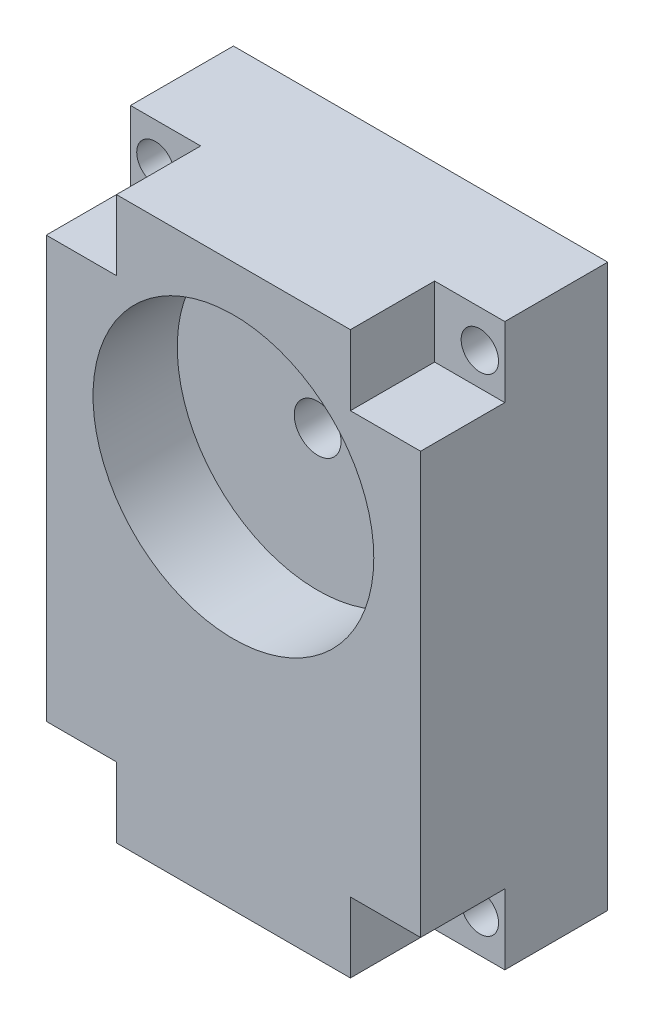
SolidWorks part; units mm, degrees
ref_plane "Front Plane" through (0, 0, 0) normal (0, 0, 1) x (1, 0, 0)
ref_plane "Top Plane" through (0, 0, 0) normal (0, 1, 0) x (1, 0, 0)
ref_plane "Right Plane" through (0, 0, 0) normal (1, 0, 0) x (0, 0, -1)
sketch "Sketch1" plane through (0, 0, 0) normal (0, 0, 1) x (1, 0, 0)
  line L1 (20, -30) -> (-20, -30)
  line L2 (20, -30) -> (20, 30)
  line L3 (20, 30) -> (-20, 30)
  line L4 (-20, -30) -> (-20, 30)
  line L5 (20, -30) -> (-20, 30) construction
  line L6 (20, 30) -> (-20, -30) construction
  point P0 (0, 0)
  dimension "D1" = 40
  dimension "D2" = 60
extrude "Boss-Extrude1" add sketch "Sketch1" along normal blind 20
sketch "Sketch2" plane through (0, 0, 20) normal (0, 0, 1) x (1, 0, 0)
  line L0 (-20, 0) -> (20, 0) construction
  line L1 (-20, 30) -> (-20, -30) construction
  line L2 (20, -30) -> (20, 30) construction
  line L3 (20, 0) -> (0, 0) construction
  line L4 (0, 0) -> (0, 20.25) construction
  circle A0 centre (0, 10.125) radius 15
  dimension "D2" = 30
  dimension "D1" = 20.25
extrude "Cut-Extrude1" cut sketch "Sketch2" against normal blind 9
sketch "Sketch3" plane through (0, 0, 11) normal (0, 0, 1) x (1, 0, 0)
  line L5 (10, -20.25) -> (-10, 20.25) construction
  line L6 (10, 20.25) -> (-10, -20.25) construction
  line L7 (0, 0) -> (20, 30) construction
  line L8 (20, 30) -> (20, 0) construction
  line L9 (20, -30) -> (20, 30) construction
  line L10 (20, 0) -> (0, 0) construction
  line L11 (0, 0) -> (0, 13.6402) construction
  line L12 (0, 0) -> (0, 20.25) construction
  line L13 (20, 30) -> (-20, 30) construction
  line L14 (10, 15) -> (10, 20.25)
  circle A0 centre (17.3333, 26) radius 2
  circle A1 centre (-17.3333, 26) radius 2
  circle A2 centre (17.3333, -26) radius 2
  circle A3 centre (-17.3333, -26) radius 2
  point P0 (0, 0)
  dimension "D3" = 4
  dimension "D4" = 4
  dimension "D1" = 40.5
  dimension "D2" = 20
extrude "Cut-Extrude2" cut sketch "Sketch3" against normal blind 32 contours A1 | A2 | A3 | A0
sketch "Sketch4" plane through (0, 0, 20) normal (0, 0, 1) x (1, 0, 0)
  line L0 (0, -16.9267) -> (0, 16.9267) construction
  line L1 (0, 16.9267) -> (0, -16.9267) construction
  line L2 (0, 0) -> (17.9224, 0) construction
  line L3 (-27.5, 37.5) -> (-12.5, 37.5)
  line L4 (27.5, 37.5) -> (12.5, 37.5)
  line L5 (27.5, 37.5) -> (27.5, 22.5)
  line L6 (27.5, 22.5) -> (12.5, 22.5)
  line L7 (12.5, 37.5) -> (12.5, 22.5)
  line L8 (27.5, 37.5) -> (12.5, 22.5) construction
  line L9 (27.5, 22.5) -> (12.5, 37.5) construction
  line L10 (-27.5, 22.5) -> (-12.5, 37.5) construction
  line L11 (-27.5, 22.5) -> (-12.5, 22.5)
  line L12 (-27.5, 37.5) -> (-27.5, 22.5)
  line L13 (-12.5, 37.5) -> (-12.5, 22.5)
  line L14 (-27.5, -22.5) -> (-12.5, -37.5) construction
  line L15 (27.5, -22.5) -> (12.5, -37.5) construction
  line L16 (27.5, -37.5) -> (12.5, -22.5) construction
  line L17 (-12.5, -37.5) -> (-12.5, -22.5)
  line L18 (-27.5, -37.5) -> (-27.5, -22.5)
  line L19 (-27.5, -22.5) -> (-12.5, -22.5)
  line L20 (12.5, -37.5) -> (12.5, -22.5)
  line L21 (27.5, -22.5) -> (12.5, -22.5)
  line L22 (27.5, -37.5) -> (27.5, -22.5)
  line L23 (27.5, -37.5) -> (12.5, -37.5)
  line L24 (-27.5, -37.5) -> (-12.5, -37.5)
  point P3 (20, 30)
  point P23 (20, -30)
  dimension "D1" = 15
  dimension "D2" = 15
extrude "Cut-Extrude3" cut sketch "Sketch4" against normal up to surface (9 mm away) up to face at (15, 10.125, 11)
sketch "Sketch5" plane through (0, 0, 11) normal (0, 0, 1) x (1, 0, 0)
  circle A0 centre (0, 10.125) radius 2.5
  dimension "D1" = 5
extrude "Cut-Extrude4" cut sketch "Sketch5" against normal blind 11
